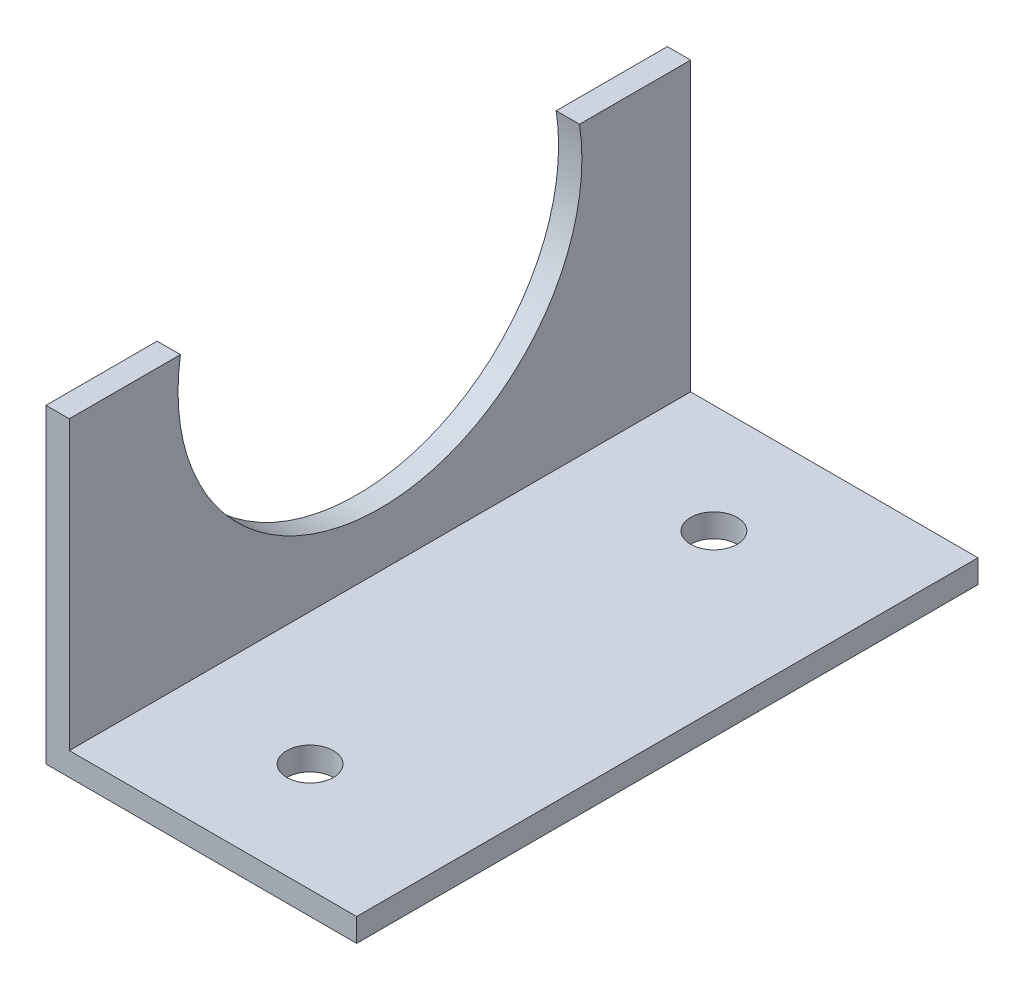
SolidWorks part; units mm, degrees
ref_plane "Plan de face" through (0, 0, 0) normal (0, 0, 1) x (1, 0, 0)
ref_plane "Plan de dessus" through (0, 0, 0) normal (0, 1, 0) x (1, 0, 0)
ref_plane "Plan de droite" through (0, 0, 0) normal (1, 0, 0) x (0, 0, -1)
sketch "Esquisse1" plane through (0, 0, 0) normal (0, 0, 1) x (1, 0, 0)
  line L0 (0, 0) -> (0, 20)
  line L1 (0, 20) -> (1.5, 20)
  line L2 (1.5, 20) -> (1.5, 1.5)
  line L3 (1.5, 1.5) -> (20, 1.5)
  line L4 (20, 1.5) -> (20, 0)
  line L5 (20, 0) -> (0, 0)
  dimension "D1" = 20
  dimension "D2" = 20
  dimension "D3" = 1.5
  dimension "D4" = 1.5
extrude "Extrusion1" add sketch "Esquisse1" along normal blind 40
sketch "Esquisse2" plane through (1.5, 0, 0) normal (1, 0, 0) x (0, 0, -1)
  line L0 (-40, 0) -> (0, 0) construction
  line L1 (0, 1.5) -> (0, 20) construction
  circle A0 centre (-20, 18) radius 13
  dimension "D2" = 18
  dimension "D3" = 20
extrude "Extrusion2" cut sketch "Esquisse2" against normal blind 30
sketch "Esquisse3" plane through (0, 1.5, 0) normal (0, 1, 0) x (-1, 0, 0)
  line L0 (-20, 40) -> (-20, 0) construction
  line L1 (-20, 40) -> (-1.5, 40) construction
  line L2 (-20, 0) -> (-1.5, 0) construction
  circle A0 centre (-10, 33) radius 1.5
  circle A1 centre (-10, 7) radius 1.5
  dimension "D1" = 10
  dimension "D3" = 7
  dimension "D2" = 7
extrude "Extrusion3" cut sketch "Esquisse3" against normal through all
